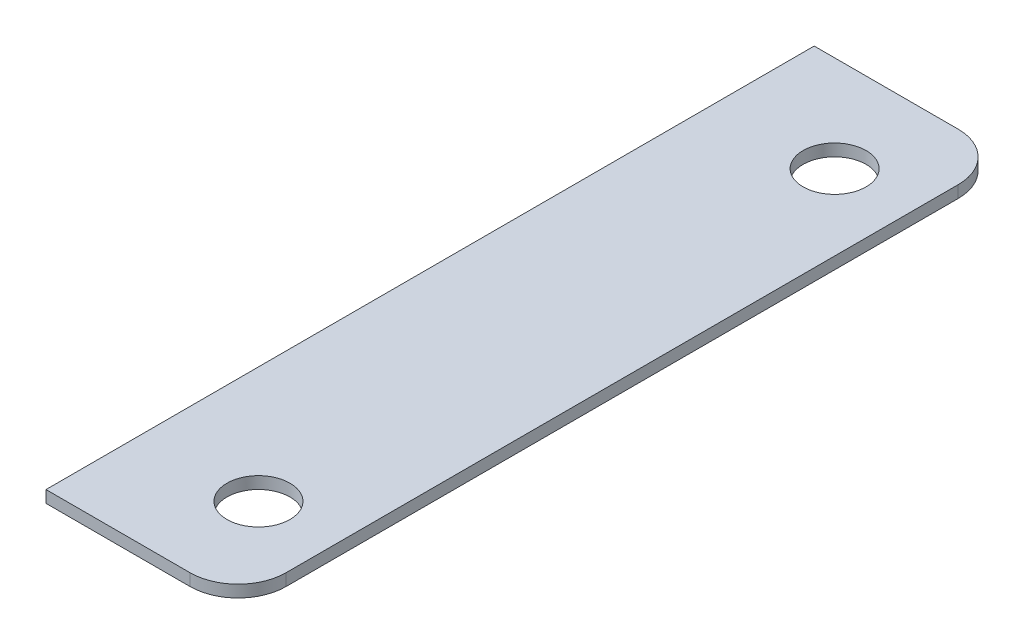
SolidWorks part; units mm, degrees
ref_plane "Front" through (0, 0, 0) normal (0, 0, 1) x (1, 0, 0)
ref_plane "Top" through (0, 0, 0) normal (0, 1, 0) x (1, 0, 0)
ref_plane "Right" through (0, 0, 0) normal (1, 0, 0) x (0, 0, -1)
sketch "Sketch1" plane through (0, 0, 0) normal (0, 1, 0) x (1, 0, 0)
  line L1 (-12.7, 50.8) -> (12.7, 50.8)
  line L2 (-12.7, 50.8) -> (-12.7, -50.8)
  line L3 (-12.7, -50.8) -> (12.7, -50.8)
  line L4 (12.7, 50.8) -> (12.7, -50.8)
  line L5 (-12.7, 50.8) -> (12.7, -50.8) construction
  line L6 (-12.7, -50.8) -> (12.7, 50.8) construction
  point P0 (0, 0)
  dimension "D1" = 101.6
  dimension "D2" = 25.4
extrude "Boss-Extrude1" add sketch "Sketch1" along normal blind 1.5875
fillet "Fillet2" radius 6.35 2 edges at (12.7, 0.7937, 50.8) (12.7, 0.7937, -50.8)
sketch "Sketch2" plane through (0, 1.5875, 0) normal (0, 1, 0) x (1, 0, 0)
  line L0 (2.7, 50.8) -> (2.7, -50.8) construction
  line L1 (6.35, 50.8) -> (-12.7, 50.8) construction
  line L2 (-12.7, -50.8) -> (6.35, -50.8) construction
  line L3 (-12.7, 0) -> (12.7, 0) construction
  line L4 (-12.7, 50.8) -> (-12.7, -50.8) construction
  line L5 (12.7, -44.45) -> (12.7, 44.45) construction
  circle A0 centre (2.7, 38.1) radius 4.165
  circle A1 centre (2.7, -38.1) radius 4.165
  dimension "D1" = 8.33
  dimension "D3" = 12.7
  dimension "D2" = 10
extrude "Cut-Extrude1" cut sketch "Sketch2" against normal up to next
